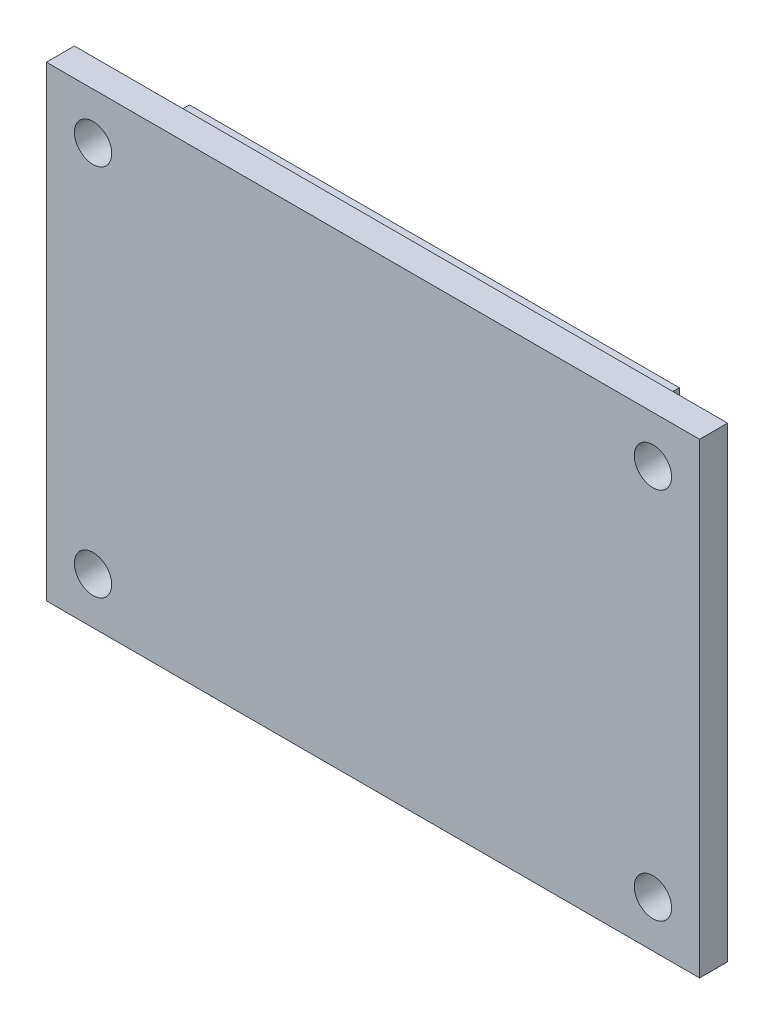
SolidWorks part; units mm, degrees
ref_plane "Front Plane" through (0, 0, 0) normal (0, 0, 1) x (1, 0, 0)
ref_plane "Top Plane" through (0, 0, 0) normal (0, 1, 0) x (1, 0, 0)
ref_plane "Right Plane" through (0, 0, 0) normal (1, 0, 0) x (0, 0, -1)
ref_plane "Plane1" through (0, 0, -23) normal (0, 0, 1) x (1, 0, 0)
sketch "Sketch1" plane through (0, 0, -23) normal (0, 0, 1) x (1, 0, 0)
  line L0 (67.3825, -50.8048) -> (-71.154, -50.8048) construction
  line L1 (20.1714, -40.8048) -> (-49.8286, -40.8048)
  line L2 (20.1714, -40.8048) -> (20.1714, 9.1952)
  line L3 (20.1714, 9.1952) -> (-49.8286, 9.1952)
  line L4 (-49.8286, -40.8048) -> (-49.8286, 9.1952)
  line L5 (-69.8286, 44.4076) -> (-69.8286, -47.4806) construction
  line L6 (15.1714, -35.8048) -> (-44.8286, -35.8048)
  line L7 (-44.8286, -35.8048) -> (-44.8286, 4.1952)
  line L8 (15.1714, 4.1952) -> (-44.8286, 4.1952)
  line L9 (15.1714, -35.8048) -> (15.1714, 4.1952)
  circle A0 centre (15.1714, -35.8048) radius 2
  circle A1 centre (-44.8286, -35.8048) radius 2
  circle A2 centre (-44.8286, 4.1952) radius 2
  circle A3 centre (15.1714, 4.1952) radius 2
  dimension "D6" = 4
  dimension "D7" = 4
  dimension "D8" = 4
  dimension "D9" = 4
  dimension "D1" = 50
  dimension "D2" = 70
  dimension "D3" = 10
  dimension "D4" = 20
  dimension "D5" = 5
extrude "Boss-Extrude1" add sketch "Sketch1" against normal blind 3 contours L4 L1 L2 L3 A3 L9 A0 L6 A1 L7 A2 L8 | A3 L8 A2 L7 A1 L6 A0 L9
sketch "Sketch2" plane through (0, 0, -26) normal (0, 0, -1) x (-1, 0, 0)
  line L0 (-20.1714, -40.8048) -> (49.8286, -40.8048) construction
  line L1 (-10.1714, -10.8048) -> (42.3286, -10.8048)
  line L2 (-10.1714, -10.8048) -> (-10.1714, 5.0652)
  line L3 (-10.1714, 5.0652) -> (42.3286, 5.0652)
  line L4 (42.3286, -10.8048) -> (42.3286, 5.0652)
  line L5 (-20.1714, -40.8048) -> (-20.1714, 9.1952) construction
  dimension "D1" = 15.87
  dimension "D2" = 52.5
  dimension "D3" = 30
  dimension "D4" = 10
extrude "Boss-Extrude2" add sketch "Sketch2" along normal blind 4.83
